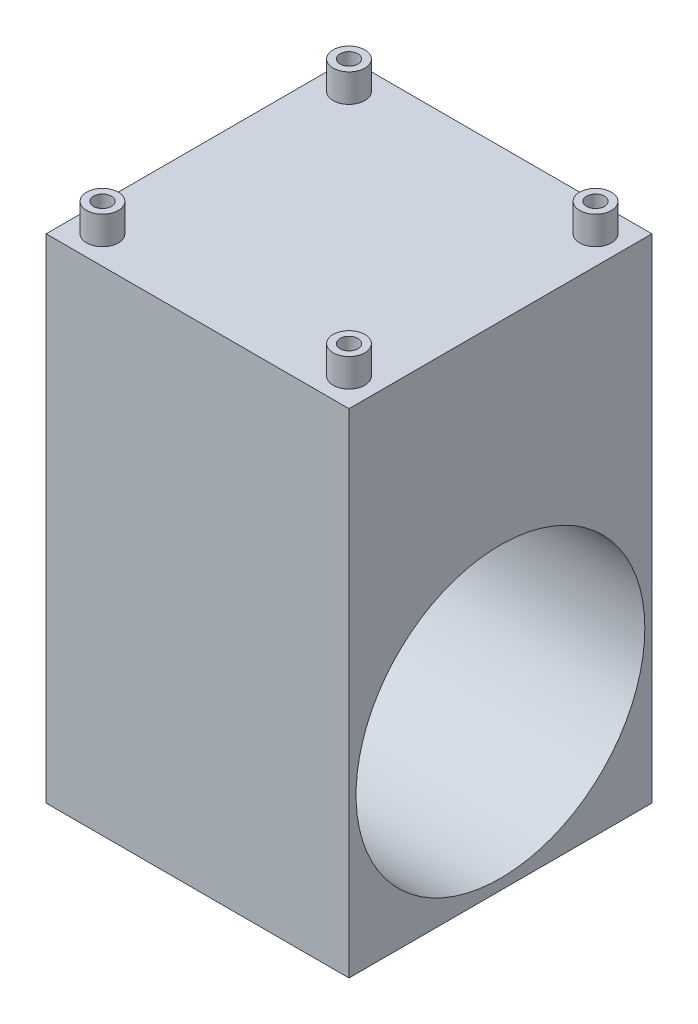
SolidWorks part; units mm, degrees
ref_plane "Front Plane" through (0, 0, 0) normal (0, 0, 1) x (1, 0, 0)
ref_plane "Top Plane" through (0, 0, 0) normal (0, 1, 0) x (1, 0, 0)
ref_plane "Right Plane" through (0, 0, 0) normal (1, 0, 0) x (0, 0, -1)
sketch "Sketch1" plane through (0, 0, 0) normal (0, 1, 0) x (1, 0, 0)
  line L1 (-21.5, 21.5) -> (21.5, 21.5)
  line L2 (-21.5, 21.5) -> (-21.5, -21.5)
  line L3 (-21.5, -21.5) -> (21.5, -21.5)
  line L4 (21.5, 21.5) -> (21.5, -21.5)
  line L5 (-21.5, 21.5) -> (21.5, -21.5) construction
  line L6 (-21.5, -21.5) -> (21.5, 21.5) construction
  point P0 (0, 0)
  dimension "D1" = 43
extrude "Boss-Extrude1" add sketch "Sketch1" along normal blind 70
sketch "Sketch2" plane through (21.5, 0, 0) normal (1, 0, 0) x (0, 0, -1)
  line L0 (0, 0) -> (0, 22) construction
  circle A0 centre (0, 22) radius 20.5
  dimension "D2" = 41
  dimension "D1" = 22
extrude "Cut-Extrude1" cut sketch "Sketch2" against normal blind 40
sketch "Sketch3" plane through (0, 70, 0) normal (0, 1, 0) x (1, 0, 0)
  line L1 (-17.5, 17.5) -> (17.5, 17.5) construction
  line L2 (-17.5, 17.5) -> (-17.5, -17.5) construction
  line L3 (-17.5, -17.5) -> (17.5, -17.5) construction
  line L4 (17.5, 17.5) -> (17.5, -17.5) construction
  line L5 (-17.5, 17.5) -> (17.5, -17.5) construction
  line L6 (-17.5, -17.5) -> (17.5, 17.5) construction
  circle A0 centre (17.5, 17.5) radius 2.25
  circle A1 centre (-17.5, 17.5) radius 2.25
  circle A2 centre (-17.5, -17.5) radius 2.25
  circle A3 centre (17.5, -17.5) radius 2.25
  circle A4 centre (-17.5, 17.5) radius 1.27
  circle A5 centre (17.5, 17.5) radius 1.27
  circle A6 centre (17.5, -17.5) radius 1.27
  circle A7 centre (-17.5, -17.5) radius 1.27
  point P0 (0, 0)
  dimension "D2" = 4.5
  dimension "D3" = 2.54
  dimension "D1" = 35
extrude "Boss-Extrude2" add sketch "Sketch3" along normal blind 4
